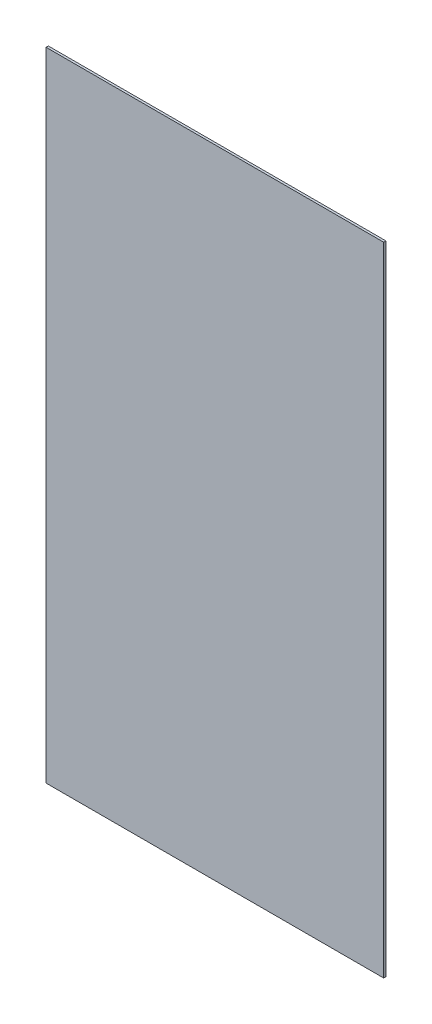
SolidWorks part; units mm, degrees
ref_plane "Front Plane" through (0, 0, 0) normal (0, 0, 1) x (1, 0, 0)
ref_plane "Top Plane" through (0, 0, 0) normal (0, 1, 0) x (1, 0, 0)
ref_plane "Right Plane" through (0, 0, 0) normal (1, 0, 0) x (0, 0, -1)
sketch "Sketch1" plane through (0, 0, 0) normal (0, 0, 1) x (1, 0, 0)
  line L1 (-89.5, 9.5) -> (89.5, 9.5)
  line L2 (-89.5, 9.5) -> (-89.5, -328.5)
  line L3 (-89.5, -328.5) -> (89.5, -328.5)
  line L4 (89.5, 9.5) -> (89.5, -328.5)
  point P4 (0, 0)
  point P6 (0, 0)
extrude "Boss-Extrude1" add sketch "Sketch1" along normal blind 1.2
